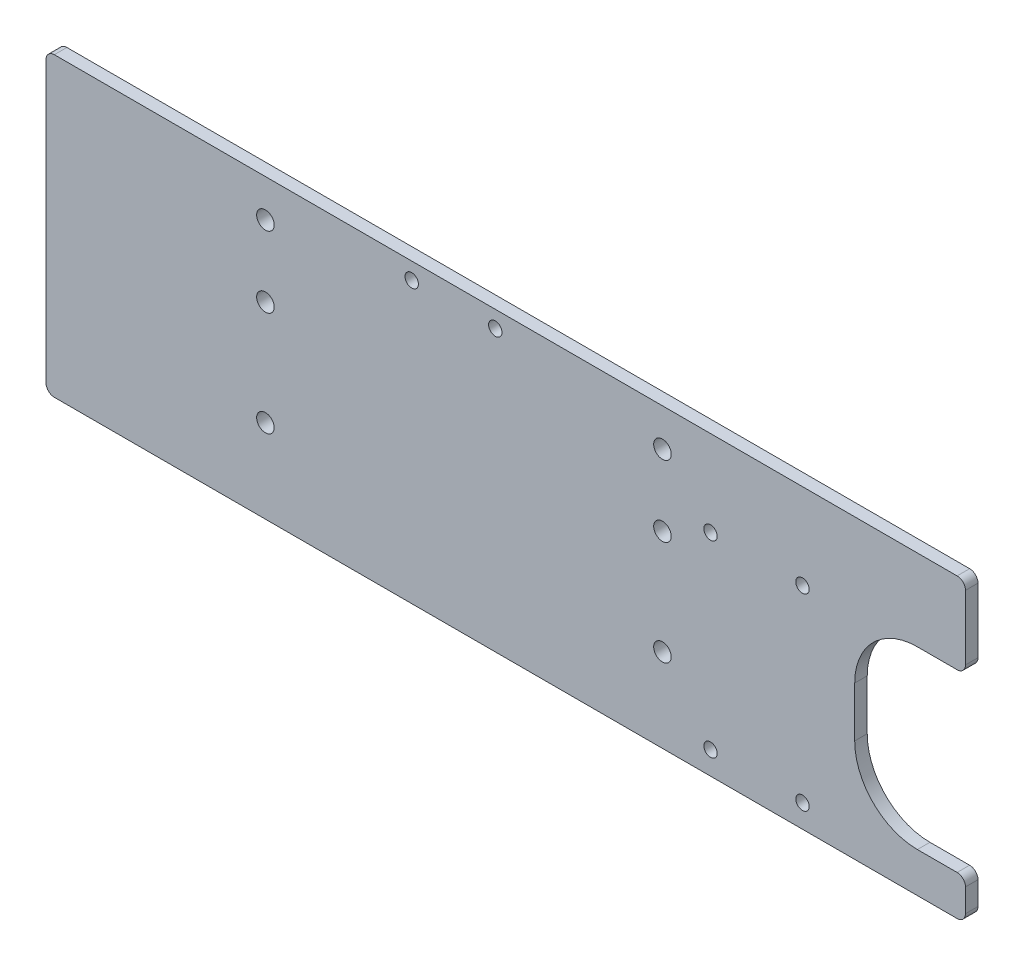
SolidWorks part; units mm, degrees
material "Thornel Mat VMA"
ref_plane "前视基准面" through (0, 0, 0) normal (0, 0, 1) x (1, 0, 0)
ref_plane "上视基准面" through (0, 0, 0) normal (0, 1, 0) x (1, 0, 0)
ref_plane "右视基准面" through (0, 0, 0) normal (1, 0, 0) x (0, 0, -1)
other "Configuration Table"
sketch "草图1" plane through (0, 0, 0) normal (0, 0, 1) x (1, 0, 0)
  line L0 (0, 0) -> (0, -50000) construction
  line L2 (0, 0) -> (50000, 0) construction
  line L3 (-100, 27) -> (100, 27)
  line L4 (-100, 27) -> (-100, -27)
  line L5 (-100, -27) -> (100, -27)
  line L6 (100, 27) -> (100, -27)
  line L7 (-100, 27) -> (100, -27) construction
  line L8 (-100, -27) -> (100, 27) construction
  line L9 (-47.5, 21) -> (-47.5, 4) construction
  line L10 (-47.5, 4) -> (-47.5, -21) construction
  circle A3 centre (-47.5, 21) radius 2.1
  circle A4 centre (-47.5, 4) radius 2.1
  circle A5 centre (-47.5, -21) radius 2.1
  circle A6 centre (47.5, -21) radius 2.1
  circle A7 centre (47.5, 4) radius 2.1
  circle A8 centre (47.5, 21) radius 2.1
  point P0 (0, 0)
  dimension "D1" = 47.5
  dimension "D3" = 6
  dimension "D4" = 17
  dimension "D6" = 4.2
  dimension "D2" = 200
  dimension "D5" = 25
extrude "凸台-拉伸1" add sketch "草图1" along normal blind 3
sketch "草图3" plane through (0, 0, 3) normal (0, 0, 1) x (1, 0, 0)
  line L1 (-100, -27) -> (100, -27)
  line L2 (-100, -27) -> (-100, -41)
  line L3 (-100, -41) -> (100, -41)
  line L4 (100, -27) -> (100, -41)
  dimension "D1" = 14
extrude "凸台-拉伸2" add sketch "草图3" against normal up to surface (3 mm away) up to face at (0, 0, 0)
sketch "草图2" plane through (0, 0, 3) normal (0, 0, 1) x (1, 0, 0)
  line L0 (-0.7542, -13) -> (49999.2458, -13) construction
  line L2 (59, -35.5) -> (81, -35.5) construction
  line L3 (59, -35.5) -> (59, 9.5) construction
  line L4 (59, 9.5) -> (81, 9.5) construction
  line L5 (81, -35.5) -> (81, 9.5) construction
  line L6 (59, -35.5) -> (81, 9.5) construction
  line L7 (59, 9.5) -> (81, -35.5) construction
  circle A0 centre (59, 9.5) radius 1.6
  circle A1 centre (81, 9.5) radius 1.6
  circle A2 centre (81, -35.5) radius 1.6
  circle A3 centre (59, -35.5) radius 1.6
  circle A4 centre (47.5, 21) radius 4.5 construction
  circle A5 centre (81, 9.5) radius 3 construction
  point P3 (70, -13)
  dimension "D3" = 6
  dimension "D4" = 3.2
  dimension "D6" = 9
  dimension "D1" = 45
  dimension "D2" = 22
  dimension "D5" = 13
  dimension "D7" = 70
extrude "切除-拉伸1" cut sketch "草图2" against normal blind 10
sketch "草图7" plane through (0, 0, 3) normal (0, 0, 1) x (1, 0, 0)
  line L0 (-100, -41) -> (100, -41) construction
  line L1 (100, 27) -> (85, 27)
  line L2 (100, 27) -> (100, -41)
  line L3 (100, -41) -> (85, -41)
  line L4 (85, 27) -> (85, -41)
  dimension "D1" = 15
extrude "切除-拉伸3" cut sketch "草图7" against normal blind 10
sketch "草图8" plane through (0, 0, 3) normal (0, 0, 1) x (1, 0, 0)
  line L0 (85, 27) -> (-100, 27) construction
  line L1 (-100, 27) -> (85, 27)
  line L2 (-100, 27) -> (-100, 30)
  line L3 (-100, 30) -> (85, 30)
  line L4 (85, 27) -> (85, 30)
  line L5 (85, 27) -> (85, -41) construction
  dimension "D1" = 3
extrude "凸台-拉伸3" add sketch "草图8" against normal up to surface (3 mm away) up to face at (60.6, -35.5, 0)
sketch "草图9" plane through (0, 0, 3) normal (0, 0, 1) x (1, 0, 0)
  line L0 (-100, 26) -> (85, 26) construction
  line L1 (-100, 30) -> (-100, -41) construction
  line L2 (85, 30) -> (85, -41) construction
  line L3 (85, 30) -> (-100, 30) construction
  line L4 (-7.5, 30) -> (-7.5, -49970) construction
  circle A0 centre (-12.5, 26) radius 1.6
  circle A1 centre (7.5, 26) radius 1.6
  point P10 (-7.5, 30)
  dimension "D2" = 3.2
  dimension "D3" = 5
  dimension "D4" = 20
  dimension "D1" = 4
extrude "切除-拉伸4" cut sketch "草图9" against normal blind 10
sketch "草图10" plane through (0, 0, 3) normal (0, 0, 1) x (1, 0, 0)
  line L0 (85, 30) -> (85, -41) construction
  line L1 (85, 30) -> (120, 30)
  line L2 (85, 30) -> (85, -41)
  line L3 (85, -41) -> (120, -41)
  line L4 (120, 30) -> (120, -41)
  line L5 (-100, -41) -> (85, -41) construction
  dimension "D1" = 35
extrude "凸台-拉伸4" add sketch "草图10" against normal up to surface (3 mm away) up to face at (-10.9, 26, 0)
sketch "草图12" plane through (0, 0, 3) normal (0, 0, 1) x (1, 0, 0)
  line L0 (120, -41) -> (120, 30) construction
  line L1 (120, 10.55) -> (93.5, 10.55)
  line L2 (120, 10.55) -> (120, -31.45)
  line L3 (120, -31.45) -> (93.5, -31.45)
  line L4 (93.5, 10.55) -> (93.5, -31.45)
  line L5 (120, 30) -> (-100, 30) construction
  dimension "D1" = 19.45
  dimension "D2" = 42
  dimension "D3" = 26.5
extrude "切除-拉伸6" cut sketch "草图12" against normal blind 10
fillet "圆角1" radius 15 2 edges at (93.5, -31.45, 1.5) (93.5, 10.55, 1.5)
fillet "圆角2" radius 2 6 edges at (120, 30, 1.5) (-100, 30, 1.5) (-100, -41, 1.5) (120, -41, 1.5) (120, -31.45, 1.5) (120, 10.55, 1.5)
